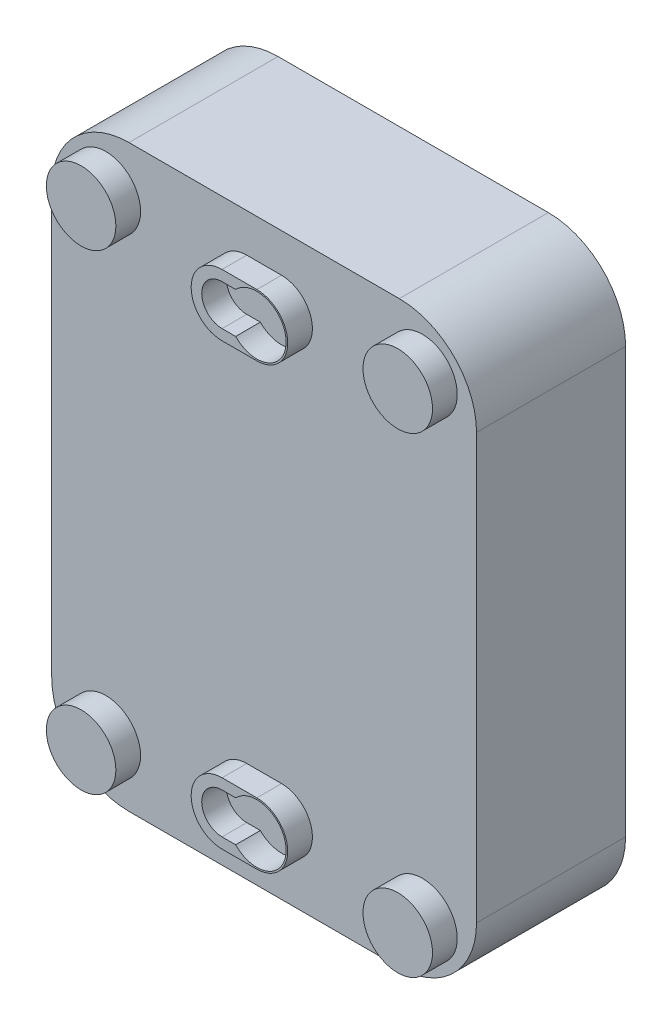
SolidWorks part; units mm, degrees
ref_plane "Front Plane" through (0, 0, 0) normal (0, 0, 1) x (1, 0, 0)
ref_plane "Top Plane" through (0, 0, 0) normal (0, 1, 0) x (1, 0, 0)
ref_plane "Right Plane" through (0, 0, 0) normal (1, 0, 0) x (0, 0, -1)
sketch "Sketch1" plane through (0, 0, 0) normal (0, 0, 1) x (1, 0, 0)
  line L1 (0, 0) -> (69.85, 0)
  line L2 (0, 0) -> (0, 95.25)
  line L3 (0, 95.25) -> (69.85, 95.25)
  line L4 (69.85, 0) -> (69.85, 95.25)
  dimension "D1" = 69.85
  dimension "D2" = 95.25
extrude "Boss-Extrude1" add sketch "Sketch1" along normal blind 28.575
fillet "Fillet1" radius 12.7 4 edges at (0, 0, 14.2875) (69.85, 0, 14.2875) (69.85, 95.25, 14.2875) (0, 95.25, 14.2875)
sketch "Sketch2" plane through (0, 0, 28.575) normal (0, 0, 1) x (1, 0, 0)
  line L0 (12.7, 0) -> (57.15, 0) construction
  line L1 (69.85, 12.7) -> (69.85, 82.55) construction
  line L2 (0, 82.55) -> (0, 12.7) construction
  line L3 (57.15, 95.25) -> (12.7, 95.25) construction
  line L4 (37.7825, 6.35) -> (32.0675, 6.35)
  line L5 (37.7825, 16.51) -> (32.0675, 16.51)
  line L6 (69.85, 47.625) -> (0, 47.625) construction
  line L7 (34.925, 0) -> (34.925, 80.4772) construction
  line L8 (37.7825, 78.74) -> (32.0675, 78.74)
  line L9 (37.7825, 88.9) -> (32.0675, 88.9)
  line L10 (32.0675, 80.4772) -> (34.3017, 80.4772)
  line L11 (32.0675, 87.1628) -> (34.3017, 87.1628)
  line L12 (34.925, 87.2384) -> (34.925, 95.25) construction
  line L13 (32.0675, 14.7728) -> (34.3017, 14.7728)
  line L14 (32.0675, 8.0872) -> (34.3017, 8.0872)
  circle A0 centre (60.96, 8.89) radius 5.715
  circle A1 centre (8.89, 8.89) radius 5.715
  circle A2 centre (8.89, 86.36) radius 5.715
  circle A3 centre (60.96, 86.36) radius 5.715
  arc A4 (37.7825, 6.35) -> (37.7825, 16.51) centre (37.7825, 11.43) ccw
  arc A5 (32.0675, 16.51) -> (32.0675, 6.35) centre (32.0675, 11.43) ccw
  arc A6 (37.7825, 88.9) -> (37.7825, 78.74) centre (37.7825, 83.82) cw
  arc A7 (32.0675, 78.74) -> (32.0675, 88.9) centre (32.0675, 83.82) cw
  arc A8 (34.3017, 80.4772) -> (34.3017, 87.1628) centre (37.7825, 83.82) ccw
  arc A9 (32.0675, 87.1628) -> (32.0675, 80.4772) centre (32.0675, 83.82) ccw
  arc A10 (32.0675, 8.0872) -> (32.0675, 14.7728) centre (32.0675, 11.43) cw
  arc A11 (34.3017, 14.7728) -> (34.3017, 8.0872) centre (37.7825, 11.43) cw
  dimension "D1" = 11.43
  dimension "D2" = 2.8575
  dimension "D13" = 9.652
  dimension "D3" = 5.715
  dimension "D4" = 8.89
  dimension "D5" = 8.89
  dimension "D6" = 8.89
  dimension "D7" = 8.89
  dimension "D8" = 8.89
  dimension "D9" = 8.89
  dimension "D10" = 8.89
  dimension "D11" = 8.89
  dimension "D12" = 6.35
extrude "Cut-Extrude1" cut sketch "Sketch2" against normal blind 4.064 flip side to cut
